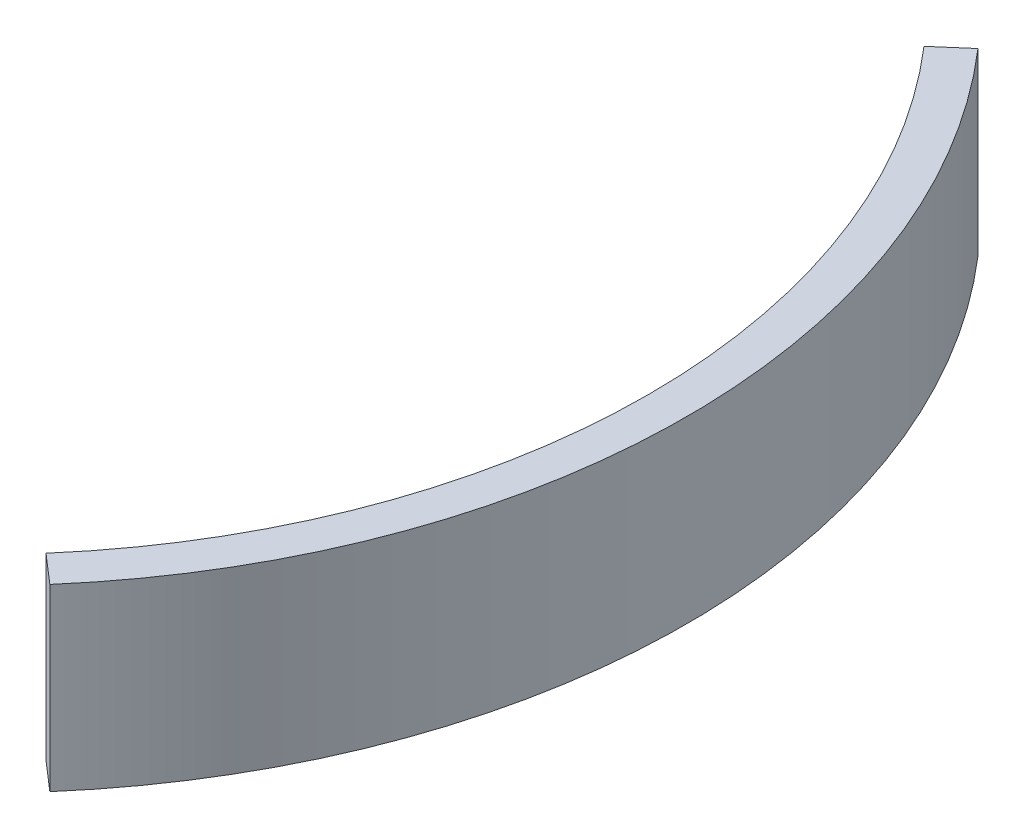
SolidWorks part; units mm, degrees
ref_plane "Front Plane" through (0, 0, 0) normal (0, 0, 1) x (1, 0, 0)
ref_plane "Top Plane" through (0, 0, 0) normal (0, 1, 0) x (1, 0, 0)
ref_plane "Right Plane" through (0, 0, 0) normal (1, 0, 0) x (0, 0, -1)
sketch "Sketch1" plane through (0, 0, 0) normal (0, 1, 0) x (1, 0, 0)
  line L0 (-1000, 0) -> (49000, 0) construction
  line L1 (0, -1000) -> (0, 49000) construction
  line L2 (42.3114, 36.6844) -> (44.7292, 38.7806)
  line L4 (44.7292, -38.7806) -> (42.3114, -36.6844)
  arc A4 (0, -56) -> (0, 56) centre (0, 0) ccw construction
  arc A5 (42.3114, 36.6844) -> (42.3114, -36.6844) centre (0, 0) cw
  arc A6 (44.7292, 38.7806) -> (44.7292, -38.7806) centre (0, 0) cw
  point P3 (42.3114, 36.6844)
  point P7 (42.3114, -36.6844)
  point P12 (56, 0)
  dimension "D1" = 56
  dimension "D2" = 80
  dimension "D3" = 3.2
extrude "Boss-Extrude1" add sketch "Sketch1" along normal blind 15
